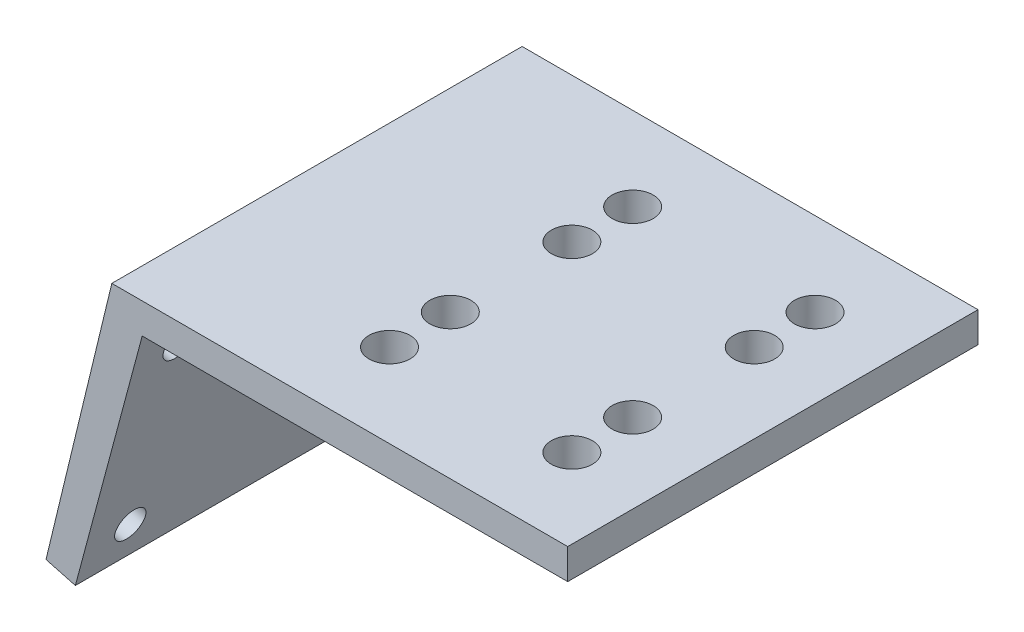
SolidWorks part; units mm, degrees
ref_plane "Front Plane" through (0, 0, 0) normal (0, 0, 1) x (1, 0, 0)
ref_plane "Top Plane" through (0, 0, 0) normal (0, 1, 0) x (1, 0, 0)
ref_plane "Right Plane" through (0, 0, 0) normal (1, 0, 0) x (0, 0, -1)
sketch "Sketch5" plane through (0, 0, 0) normal (0, 0, 1) x (1, 0, 0)
  line L0 (0, 0) -> (-30, 0)
  line L1 (0, 0) -> (0, -2)
  line L2 (-32.3999, -18.4207) -> (-34.3318, -17.9031)
  line L3 (0, -2) -> (-28, -2)
  line L4 (-28, -2) -> (-32.3999, -18.4207)
  line L5 (-34.3318, -17.9031) -> (-30, 0)
  dimension "D1" = 30
  dimension "D2" = 2
  dimension "D3" = 105
  dimension "D4" = 28
  dimension "D5" = 17
  dimension "D6" = 2
extrude "Boss-Extrude3" add sketch "Sketch5" along normal blind 27
sketch "Sketch7" plane through (0, 0, 0) normal (0, 1, 0) x (1, 0, 0)
  line L0 (-30, -13.5) -> (0, -13.5) construction
  line L1 (-30, -27) -> (-30, 0) construction
  line L2 (0, -27) -> (0, 0) construction
  line L3 (-17.2265, -13.5) -> (-17.2265, -5.5) construction
  line L4 (-5.2265, -13.5) -> (-5.2265, -5.5) construction
  circle A0 centre (-17.2265, -5.5) radius 1.35
  circle A1 centre (-17.2265, -9.5) radius 1.35
  circle A2 centre (-5.2265, -5.5) radius 1.35
  circle A3 centre (-5.2265, -9.5) radius 1.35
  circle A4 centre (-5.2265, -17.5) radius 1.35
  circle A5 centre (-5.2265, -21.5) radius 1.35
  circle A6 centre (-17.2265, -17.5) radius 1.35
  circle A7 centre (-17.2265, -21.5) radius 1.35
  dimension "D1" = 2.7
  dimension "D2" = 2.7
  dimension "D8" = 2.7
  dimension "D9" = 2.7
  dimension "D3" = 8
  dimension "D4" = 12.7735
  dimension "D5" = 4
  dimension "D6" = 8
  dimension "D7" = 12
  dimension "D10" = 4
extrude "Cut-Extrude2" cut sketch "Sketch7" against normal blind 20
sketch "Sketch8" plane through (-28.3408, 6.8573, 0) normal (-0.972, 0.2352, 0) x (0, 0, 1)
  line L0 (13.5, -7.0551) -> (13.5, -10.8551) construction
  line L1 (27, -7.0551) -> (0, -7.0551) construction
  line L2 (13.5, -10.8551) -> (3, -10.8551) construction
  line L3 (13.5, -10.8551) -> (13.5, -25.4748) construction
  line L4 (27, -25.4748) -> (0, -25.4748) construction
  line L5 (3, -10.8551) -> (3, -23.1551) construction
  circle A0 centre (3, -10.8551) radius 1
  circle A1 centre (3, -23.1551) radius 1
  circle A2 centre (24, -23.1551) radius 1
  circle A3 centre (24, -10.8551) radius 1
  dimension "D3" = 2
  dimension "D5" = 2
  dimension "D1" = 3.8
  dimension "D2" = 10.5
  dimension "D4" = 12.3
extrude "Cut-Extrude3" cut sketch "Sketch8" against normal blind 20
